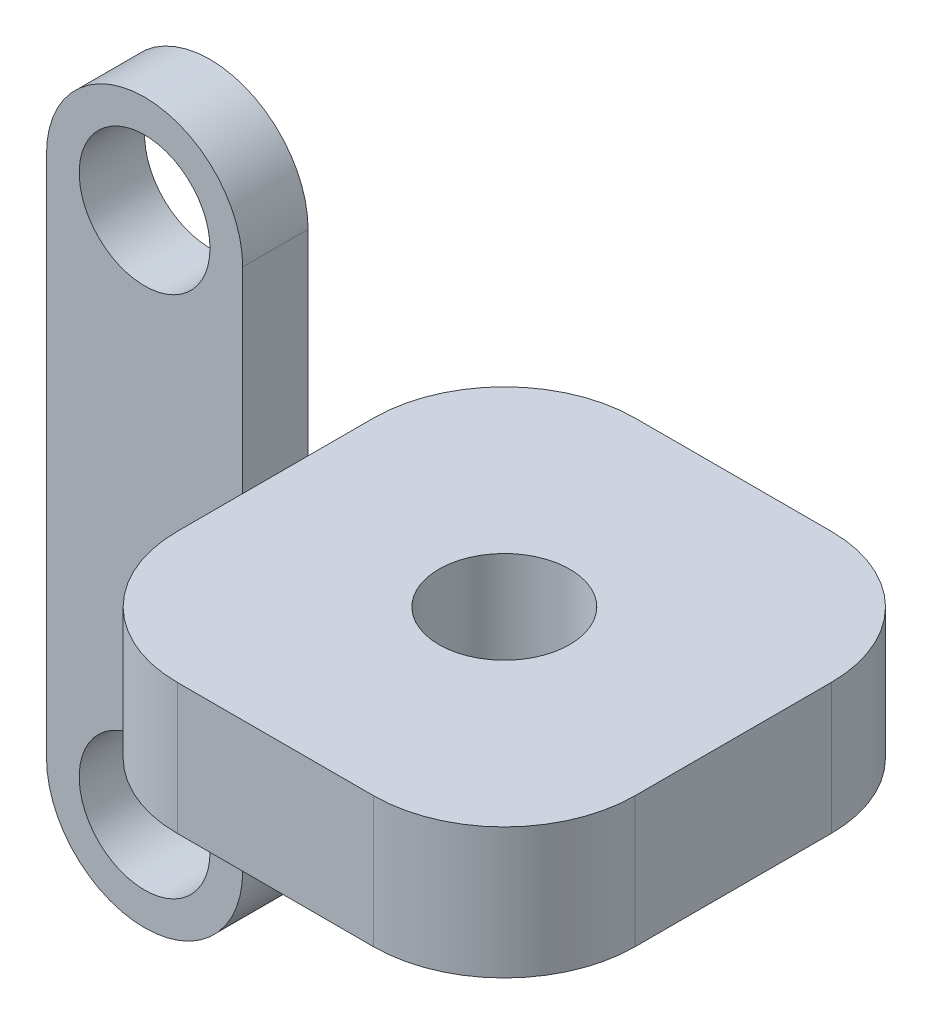
SolidWorks part; units mm, degrees
ref_plane "前视基准面" through (0, 0, 0) normal (0, 0, 1) x (1, 0, 0)
ref_plane "上视基准面" through (0, 0, 0) normal (0, 1, 0) x (1, 0, 0)
ref_plane "右视基准面" through (0, 0, 0) normal (1, 0, 0) x (0, 0, -1)
other "Configuration Table"
sketch "草图1" plane through (0, 0, 0) normal (0, 0, 1) x (1, 0, 0)
  line L0 (-7.5, 20) -> (-7.5, -20) construction
  line L1 (0, 20) -> (0, -20)
  line L2 (-15, 20) -> (-15, -20)
  arc A0 (0, 20) -> (-15, 20) centre (-7.5, 20) ccw
  arc A1 (-15, -20) -> (0, -20) centre (-7.5, -20) ccw
  point P2 (-7.5, 0)
  point P7 (0, 0)
  dimension "D2" = 7.5
  dimension "D1" = 40
extrude "凸台-拉伸1" add sketch "草图1" along normal blind 5
sketch "草图2" plane through (0, 0, 5) normal (0, 0, 1) x (1, 0, 0)
  circle A0 centre (-7.5, 20) radius 5
  circle A1 centre (-7.5, -20) radius 5
  dimension "D1" = 10
extrude "切除-拉伸1" cut sketch "草图2" against normal through all
sketch "草图3" plane through (0, 0, 0) normal (0, 1, 0) x (1, 0, 0)
  line L0 (0, 0) -> (-15, 0) construction
  line L1 (0, 15) -> (35, 15)
  line L2 (0, 15) -> (0, -20)
  line L3 (0, -20) -> (35, -20)
  line L4 (35, 15) -> (35, -20)
  line L5 (-15, -5) -> (0, -5) construction
  dimension "D1" = 15
  dimension "D2" = 15
  dimension "D3" = 35
extrude "凸台-拉伸2" add sketch "草图3" along normal mid plane 10
fillet "圆角1" radius 10 4 edges at (0, 0, -15) (35, 0, -15) (0, 0, 20) (35, 0, 20)
sketch "草图4" plane through (0, 5, 0) normal (0, 1, 0) x (1, 0, 0)
  line L0 (25, 15) -> (10, 15) construction
  line L1 (35, -10) -> (35, 5) construction
  circle A0 centre (17.5, -2.5) radius 5
  point P4 (17.5, 15)
  point P7 (35, -2.5)
  dimension "D1" = 10
extrude "切除-拉伸2" cut sketch "草图4" against normal through all
